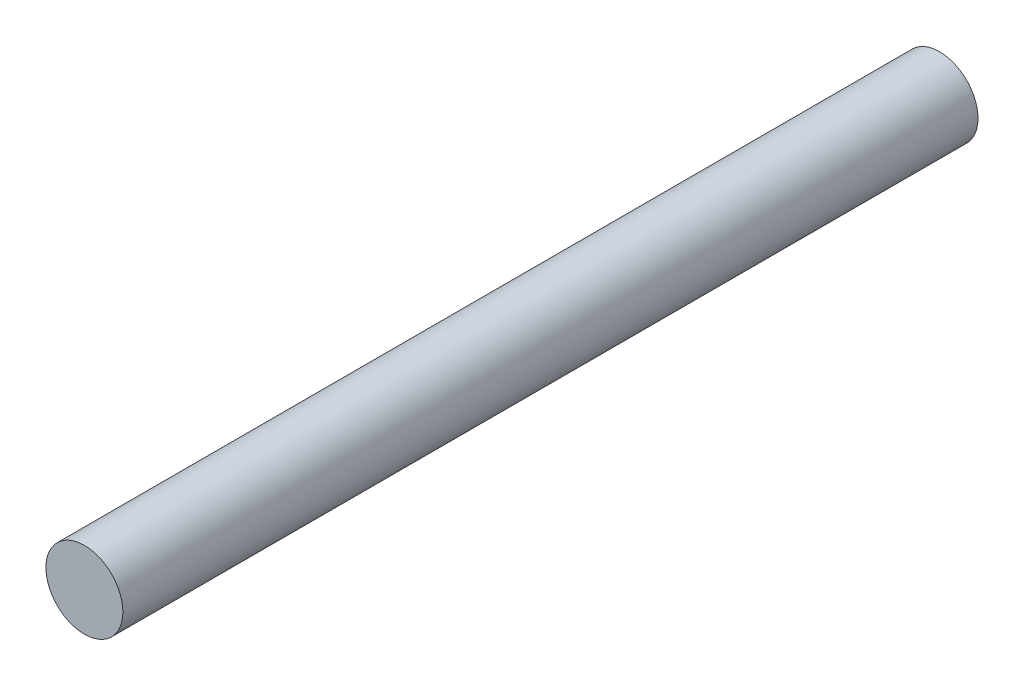
SolidWorks part; units mm, degrees
ref_plane "Front Plane" through (0, 0, 0) normal (0, 0, 1) x (1, 0, 0)
ref_plane "Top Plane" through (0, 0, 0) normal (0, 1, 0) x (1, 0, 0)
ref_plane "Right Plane" through (0, 0, 0) normal (1, 0, 0) x (0, 0, -1)
sketch "Sketch1" plane through (0, 0, 0) normal (0, 0, 1) x (1, 0, 0)
  circle A0 centre (0, 0) radius 90
  dimension "D1" = 180
extrude "Boss-Extrude1" add sketch "Sketch1" along normal blind 2000
